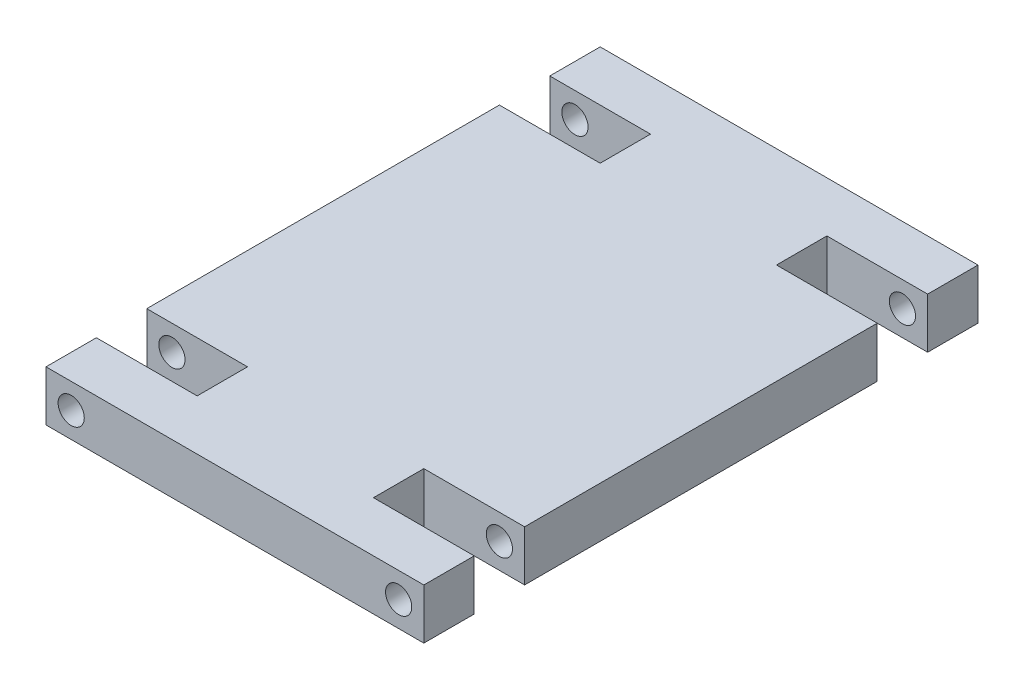
SolidWorks part; units mm, degrees
ref_plane "Alzado" through (0, 0, 0) normal (0, 0, 1) x (1, 0, 0)
ref_plane "Planta" through (0, 0, 0) normal (0, 1, 0) x (1, 0, 0)
ref_plane "Vista lateral" through (0, 0, 0) normal (1, 0, 0) x (0, 0, -1)
sketch "Croquis1" plane through (0, 0, 0) normal (0, 1, 0) x (1, 0, 0)
  line L0 (37.5, 45) -> (17.5, 45)
  line L1 (37.5, -55) -> (-37.5, -55)
  line L2 (37.5, -55) -> (37.5, -45)
  line L3 (37.5, 55) -> (-37.5, 55)
  line L4 (-37.5, -55) -> (-37.5, -45)
  line L5 (37.5, -55) -> (-37.5, 55) construction
  line L6 (37.5, 55) -> (-37.5, -55) construction
  line L7 (17.5, 45) -> (17.5, 35)
  line L8 (17.5, 35) -> (37.5, 35)
  line L9 (37.5, -35) -> (17.5, -35)
  line L10 (17.5, -35) -> (17.5, -45)
  line L11 (17.5, -45) -> (37.5, -45)
  line L12 (0, 0) -> (50000, 0) construction
  line L13 (37.5, 45) -> (37.5, 55)
  line L14 (37.5, -35) -> (37.5, 35)
  line L15 (0, 0) -> (0, 50000) construction
  line L16 (-17.5, -45) -> (-37.5, -45)
  line L17 (-17.5, -35) -> (-17.5, -45)
  line L18 (-37.5, -35) -> (-17.5, -35)
  line L19 (-37.5, -35) -> (-37.5, 35)
  line L20 (-17.5, 35) -> (-37.5, 35)
  line L21 (-17.5, 45) -> (-17.5, 35)
  line L22 (-37.5, 45) -> (-17.5, 45)
  line L23 (-37.5, 45) -> (-37.5, 55)
  point P0 (0, 0)
  dimension "D1" = 110
  dimension "D2" = 75
  dimension "D3" = 10
  dimension "D4" = 10
  dimension "D5" = 20
extrude "Saliente-Extruir1" add sketch "Croquis1" along normal mid plane 10
sketch "Croquis2" plane through (0, 0, 0) normal (0, 0, 1) x (1, 0, 0)
  line L0 (0, 0) -> (0, 50000) construction
  line L2 (37.5, 5) -> (37.5, -5) construction
  circle A0 centre (32.5, 0) radius 2.6
  circle A1 centre (-32.5, 0) radius 2.6
  point P5 (0, 0)
  dimension "D1" = 5.2
  dimension "D2" = 5
extrude "Cortar-Extruir1" cut sketch "Croquis2" against normal through all both and the other way through all
